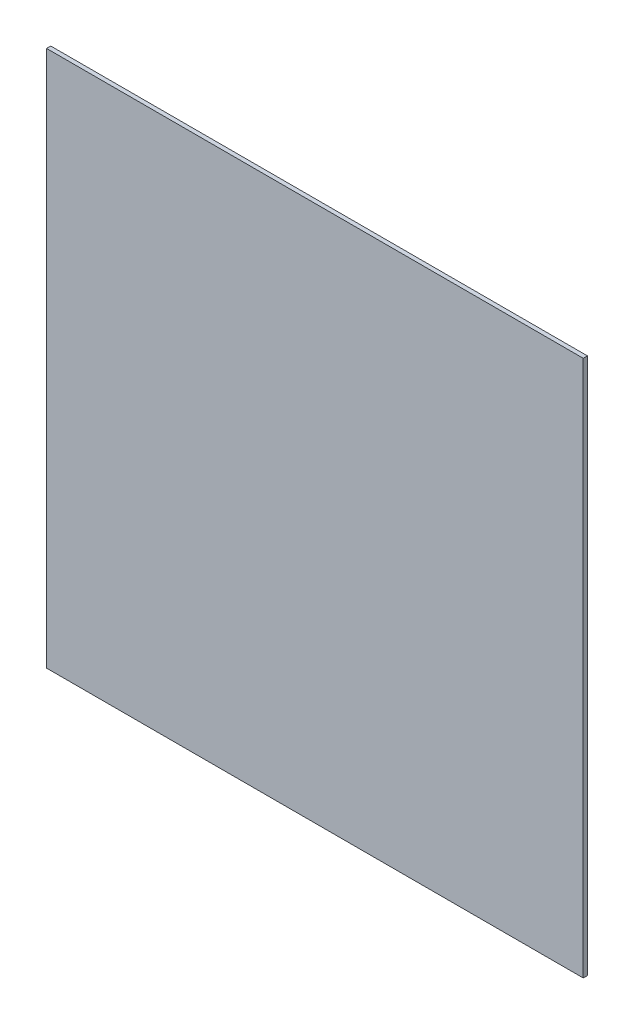
SolidWorks part; units mm, degrees
ref_plane "Front Plane" through (0, 0, 0) normal (0, 0, 1) x (1, 0, 0)
ref_plane "Top Plane" through (0, 0, 0) normal (0, 1, 0) x (1, 0, 0)
ref_plane "Right Plane" through (0, 0, 0) normal (1, 0, 0) x (0, 0, -1)
sketch "Sketch1" plane through (0, 0, 0) normal (0, 0, 1) x (1, 0, 0)
  line L1 (-304.8, -304.8) -> (304.8, -304.8)
  line L2 (-304.8, -304.8) -> (-304.8, 304.8)
  line L3 (-304.8, 304.8) -> (304.8, 304.8)
  line L4 (304.8, -304.8) -> (304.8, 304.8)
  line L5 (-304.8, -304.8) -> (304.8, 304.8) construction
  line L6 (-304.8, 304.8) -> (304.8, -304.8) construction
  point P0 (0, 0)
  dimension "D1" = 609.6
  dimension "D2" = 609.6
extrude "Boss-Extrude1" add sketch "Sketch1" along normal blind 4.7625 contours L2 L3 L4 L1
